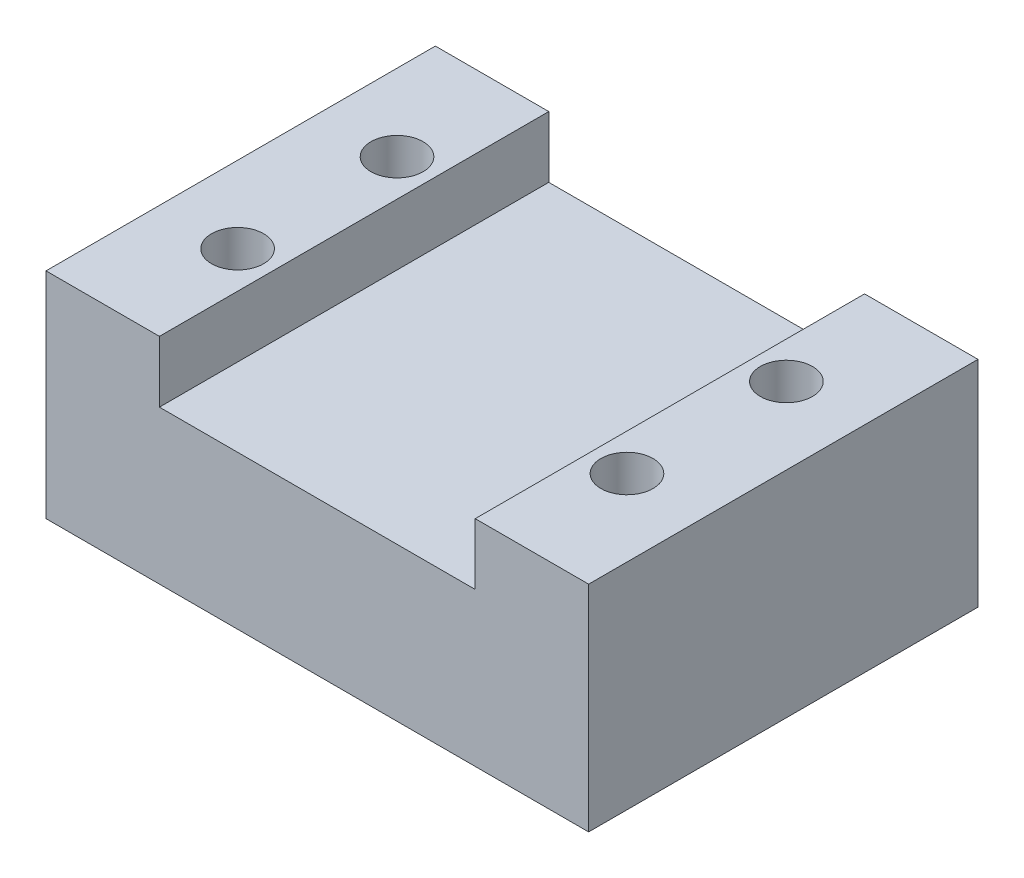
SolidWorks part; units mm, degrees
ref_plane "Front Plane" through (0, 0, 0) normal (0, 0, 1) x (1, 0, 0)
ref_plane "Top Plane" through (0, 0, 0) normal (0, 1, 0) x (1, 0, 0)
ref_plane "Right Plane" through (0, 0, 0) normal (1, 0, 0) x (0, 0, -1)
sketch "Croquis1" plane through (0, 0, 0) normal (0, 1, 0) x (1, 0, 0)
  line L1 (-17.7, -12.7) -> (17.7, -12.7)
  line L2 (-17.7, -12.7) -> (-17.7, 12.7)
  line L3 (-17.7, 12.7) -> (17.7, 12.7)
  line L4 (17.7, -12.7) -> (17.7, 12.7)
  line L5 (-17.7, -12.7) -> (17.7, 12.7) construction
  line L6 (-17.7, 12.7) -> (17.7, -12.7) construction
  point P0 (0, 0)
  dimension "D1" = 35.4
  dimension "D2" = 25.4
extrude "Saliente-Extruir1" add sketch "Croquis1" along normal blind 10
sketch "Croquis2" plane through (0, 10, 0) normal (0, 1, 0) x (1, 0, 0)
  line L1 (-17.7, -12.7) -> (-10.3, -12.7)
  line L2 (-17.7, -12.7) -> (-17.7, 12.7)
  line L3 (-17.7, 12.7) -> (-10.3, 12.7)
  line L4 (-10.3, -12.7) -> (-10.3, 12.7)
  line L5 (17.7, 12.7) -> (-17.7, 12.7) construction
  dimension "D1" = 7.4
extrude "Saliente-Extruir2" add sketch "Croquis2" along normal blind 4
mirror "Simetría1" about plane through (0, 0, 0) normal (1, 0, 0) of "Saliente-Extruir2"
sketch "Croquis8" plane through (0, 0, 0) normal (0, -1, 0) x (1, 0, 0)
  line L0 (12.7, 12.7) -> (12.7, -12.7) construction
  line L1 (-12.7, 12.7) -> (-12.7, -12.7) construction
  line L2 (17.7, 5.2) -> (-17.7, 5.2) construction
  line L3 (17.7, -5.2) -> (-17.7, -5.2) construction
  line L4 (17.7, 12.7) -> (-17.7, -12.7) construction
  point P8 (12.7, 5.2)
  point P9 (12.7, -7.5)
  point P10 (-12.7, -5.2)
  point P11 (-12.7, 5.2)
hole_wizard "Taladro de margen para M31" positions "Croquis4" profile "Croquis5" hole size "M3" standard "DIN" end condition through all
sketch "Croquis4" plane through (0, 14, 0) normal (0, 1, 0) x (1, 0, 0)
  line L0 (12.7, -12.7) -> (12.7, 12.7) construction
  line L1 (17.7, 5.2) -> (-17.7, 5.2) construction
  point P0 (-12.7, 5.2)
  point P3 (12.7, -5.2)
  point P6 (12.7, 5.2)
  point P9 (-12.7, -5.2)
sketch "Croquis5" plane through (-12.7, 14, -5.2) normal (1, 0, 0) x (0, 0, 1)
  line L0 (0, 0) -> (0, 14)
  line L1 (0, 14) -> (1.7, 14)
  line L2 (1.7, 14) -> (1.7, 0)
  line L5 (1.7, 0) -> (0, 0)
  line L11 (0, -6.35) -> (0, 107.95) construction
  dimension "Diámetro de taladro hasta el siguiente" = 3.4
  dimension "Profundidad de taladro hasta el siguiente" = 14
sketch "Croquis6" plane through (0, 0, 0) normal (0, -1, 0) x (1, 0, 0)
  line L1 (-9.7, 6.9321) -> (-12.7, 8.6641)
  line L2 (-12.7, 8.6641) -> (-15.7, 6.9321)
  line L3 (-15.7, 6.9321) -> (-15.7, 3.4679)
  line L4 (-15.7, 3.4679) -> (-12.7, 1.7359)
  line L5 (-12.7, 1.7359) -> (-9.7, 3.4679)
  line L6 (-9.7, 3.4679) -> (-9.7, 6.9321)
  line L8 (-17.7, -12.7) -> (-17.7, 12.7) construction
  circle A0 centre (-12.7, 5.2) radius 3 construction
  dimension "D1" = 6
extrude "Cortar-Extruir1" cut sketch "Croquis6" against normal blind 2
pattern_linear "MatrizL2" count 2 spacing 25.4 along (1, 0, 0) count 2 spacing 10.4 along (0, 0, -1) of "Cortar-Extruir1"
